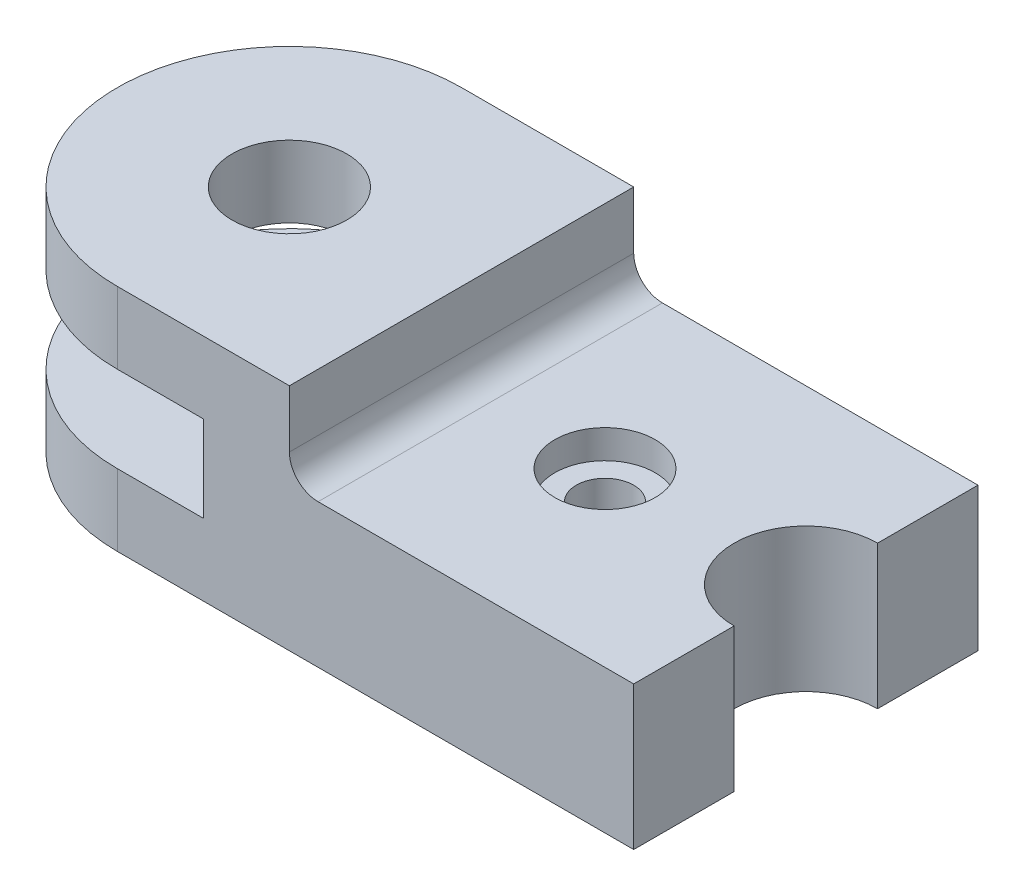
SolidWorks part; units mm, degrees
ref_plane "Front Plane" through (0, 0, 0) normal (0, 0, 1) x (1, 0, 0)
ref_plane "Top Plane" through (0, 0, 0) normal (0, 1, 0) x (1, 0, 0)
ref_plane "Right Plane" through (0, 0, 0) normal (1, 0, 0) x (0, 0, -1)
sketch "Sketch2" plane through (0, 0, 0) normal (0, 1, 0) x (1, 0, 0)
  line L0 (0, -38.1) -> (114.3, -38.1)
  line L1 (114.3, -38.1) -> (114.3, 38.1)
  line L2 (114.3, 38.1) -> (0, 38.1)
  arc A0 (0, 38.1) -> (0, -38.1) centre (0, 0) ccw
  dimension "D1" = 38.1
  dimension "D2" = 114.3
extrude "Boss-Extrude1" add sketch "Sketch2" along normal blind 50.8
sketch "Sketch3" plane through (0, 0, 38.1) normal (0, 0, 1) x (1, 0, 0)
  line L0 (38.1, 50.8) -> (38.1, 31.75)
  line L1 (0, 50.8) -> (114.3, 50.8) construction
  line L2 (38.1, 31.75) -> (114.3, 31.75)
  line L3 (114.3, 50.8) -> (114.3, 0) construction
  dimension "D1" = 19.05
  dimension "D2" = 76.2
extrude "Cut-Extrude1" cut sketch "Sketch3" against normal through all and the other way through all
fillet "Fillet1" radius 6.35 1 edges at (38.1, 31.75, 0)
sketch "Sketch5" plane through (0, 0, 38.1) normal (0, 0, 1) x (1, 0, 0)
  line L3 (19.05, 34.925) -> (19.05, 15.875)
  line L5 (19.05, 15.875) -> (0, 15.875)
  line L6 (19.05, 34.925) -> (0, 34.925)
  line L7 (19.05, 34.925) -> (-47.5157, 34.925)
  line L8 (-47.5157, 34.925) -> (-47.5157, 15.875)
  line L9 (-47.5157, 15.875) -> (19.05, 15.875)
  line M6 (0, 50.8) -> (0, 0)
extrude "Cut-Extrude2" cut sketch "Sketch5" against normal through all contours L3 L6 L5 M6 | L8 L9 L7 M6
sketch "Sketch6" plane through (0, 50.8, 0) normal (0, 1, 0) x (1, 0, 0)
  circle A0 centre (0, 0) radius 12.7
  dimension "D1" = 25.4
extrude "Cut-Extrude3" cut sketch "Sketch6" against normal through all
sketch "Sketch7" plane through (0, 31.75, 0) normal (0, 1, 0) x (1, 0, 0)
  line L0 (114.3, -38.1) -> (114.3, 38.1) construction
  circle A0 centre (114.3, 0) radius 15.875
  circle A1 centre (69.85, 0) radius 6.35
  dimension "D1" = 12.7
  dimension "D2" = 15.875
  dimension "D3" = 44.45
extrude "Cut-Extrude4" cut sketch "Sketch7" against normal through all
sketch "Sketch8" plane through (0, 31.75, 0) normal (0, 1, 0) x (1, 0, 0)
  circle A0 centre (69.85, 0) radius 11.1125
  dimension "D1" = 22.225
extrude "Cut-Extrude5" cut sketch "Sketch8" against normal blind 6.35
